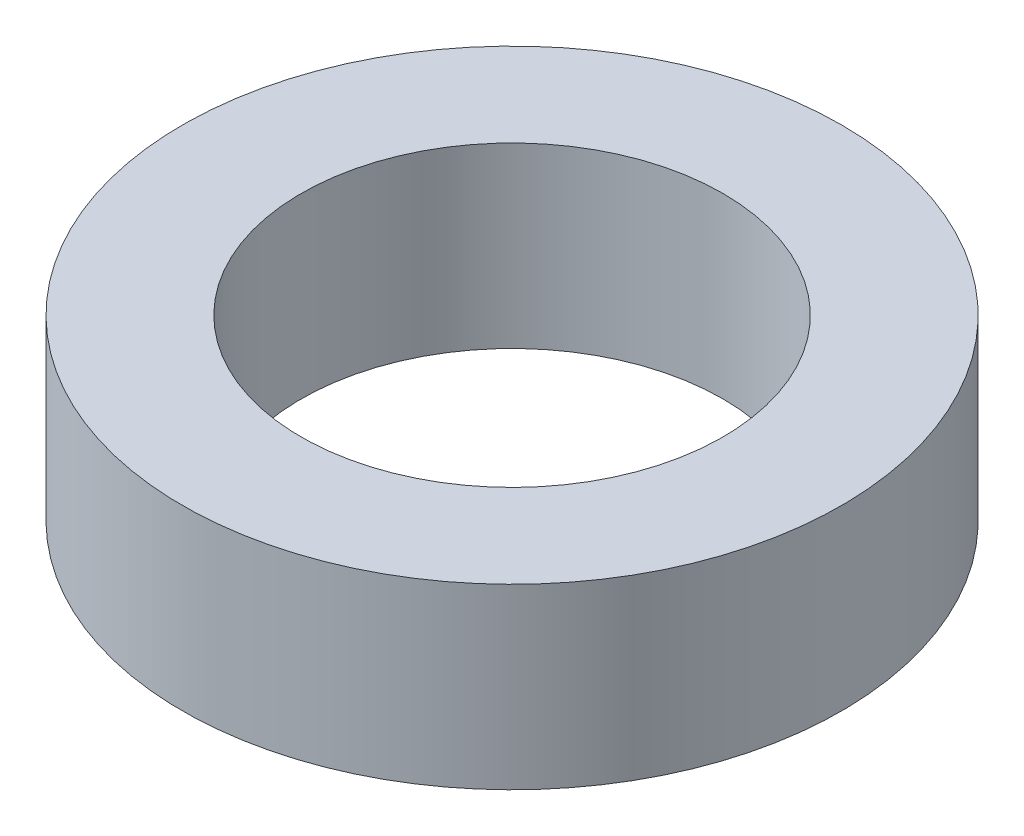
SolidWorks part; units mm, degrees
ref_plane "前视基准面" through (0, 0, 0) normal (0, 0, 1) x (1, 0, 0)
ref_plane "上视基准面" through (0, 0, 0) normal (0, 1, 0) x (1, 0, 0)
ref_plane "右视基准面" through (0, 0, 0) normal (1, 0, 0) x (0, 0, -1)
sketch "草图1" plane through (0, 0, 0) normal (0, 1, 0) x (1, 0, 0)
  circle A0 centre (0, 0) radius 1.6
  circle A1 centre (0, 0) radius 2.5
  dimension "D1" = 3.2
  dimension "D2" = 5
extrude "凸台-拉伸1" add sketch "草图1" along normal blind 1.35
